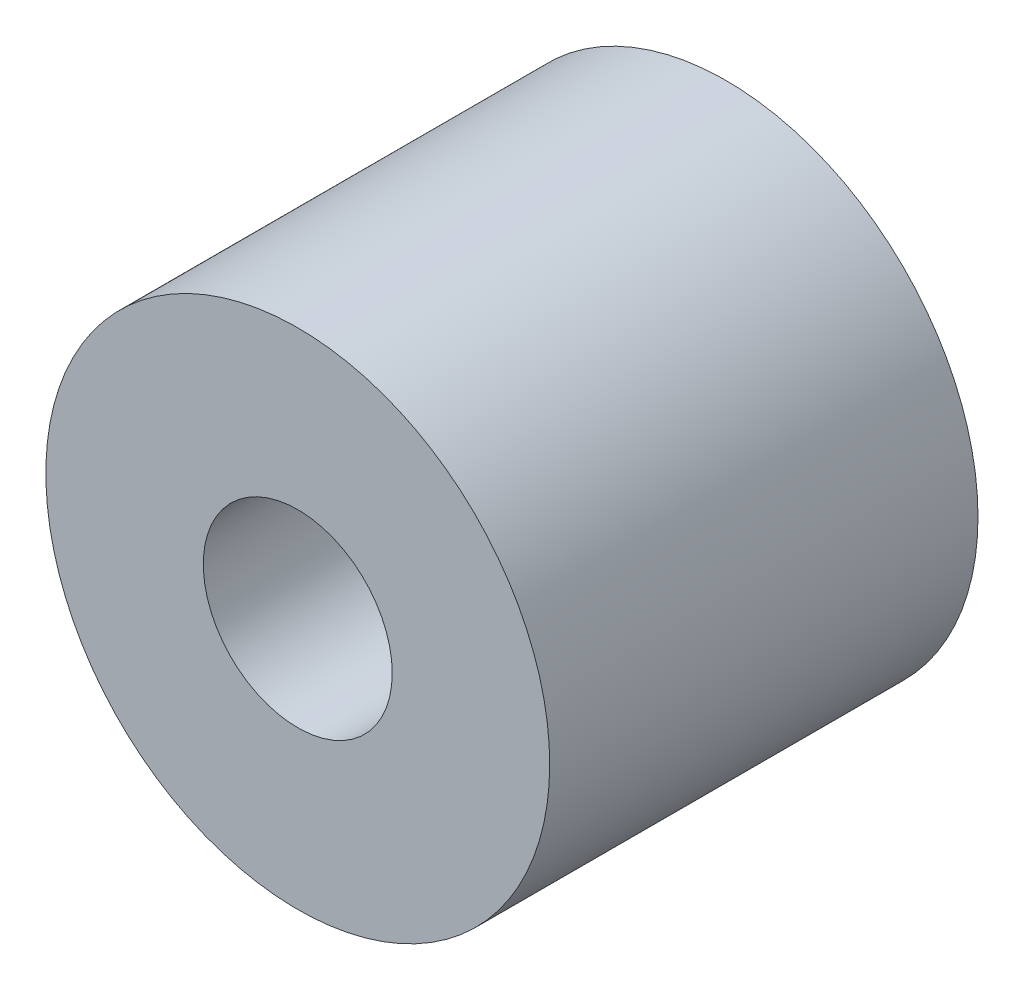
SolidWorks part; units mm, degrees
ref_plane "Front Plane" through (0, 0, 0) normal (0, 0, 1) x (1, 0, 0)
ref_plane "Top Plane" through (0, 0, 0) normal (0, 1, 0) x (1, 0, 0)
ref_plane "Right Plane" through (0, 0, 0) normal (1, 0, 0) x (0, 0, -1)
sketch "Sketch1" plane through (0, 0, 0) normal (0, 0, 1) x (1, 0, 0)
  circle A0 centre (0, 0) radius 12.7
  circle A1 centre (0, 0) radius 4.7625
  dimension "D1" = 25.4
  dimension "D2" = 9.525
extrude "Boss-Extrude1" add sketch "Sketch1" along normal blind 21.59
